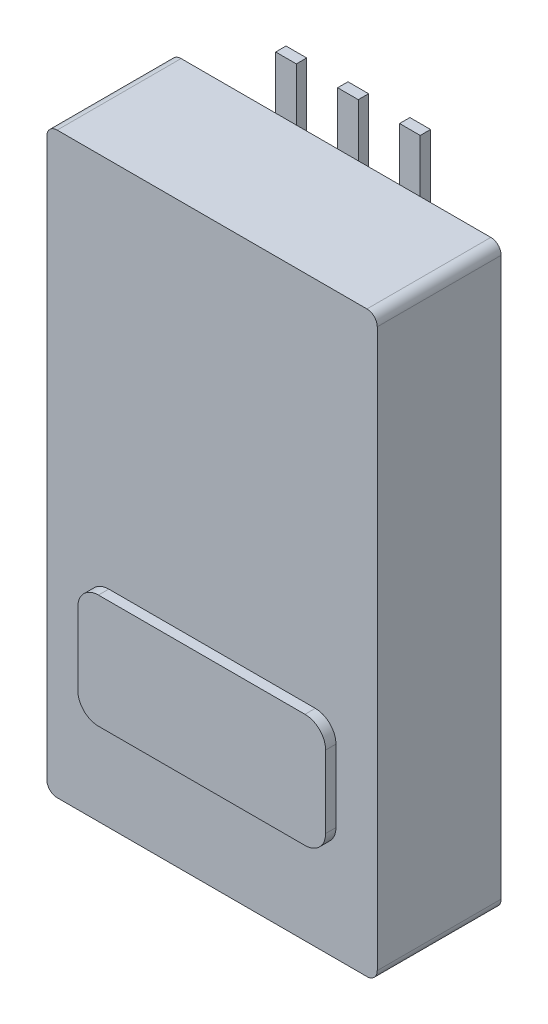
SolidWorks part; units mm, degrees
material "PE faible/moyenne densité"
ref_plane "Plan de face" through (0, 0, 0) normal (0, 0, 1) x (1, 0, 0)
ref_plane "Plan de dessus" through (0, 0, 0) normal (0, 1, 0) x (1, 0, 0)
ref_plane "Plan de droite" through (0, 0, 0) normal (1, 0, 0) x (0, 0, -1)
sketch "Esquisse1" plane through (0, 0, 0) normal (0, 0, 1) x (1, 0, 0)
  line L1 (-5.3368, 17.1111) -> (10.6632, 17.1111)
  line L2 (-5.3368, 17.1111) -> (-5.3368, -10.8889)
  line L3 (-5.3368, -10.8889) -> (10.6632, -10.8889)
  line L4 (10.6632, 17.1111) -> (10.6632, -10.8889)
  dimension "D1" = 16
  dimension "D2" = 28
extrude "Boss.-Extru.1" add sketch "Esquisse1" along normal blind 6
sketch "Esquisse2" plane through (0, 0, 6) normal (0, 0, 1) x (1, 0, 0)
  line L0 (-5.3368, -10.8889) -> (10.6632, -10.8889) construction
  line L1 (-2.3368, -0.8889) -> (7.6632, -0.8889)
  line L2 (-3.3368, -1.8889) -> (-3.3368, -5.3889)
  line L3 (-2.3368, -6.3889) -> (7.6632, -6.3889)
  line L4 (8.6632, -1.8889) -> (8.6632, -5.3889)
  line L5 (-5.3368, 17.1111) -> (-5.3368, -10.8889) construction
  arc A0 (7.6632, -0.8889) -> (8.6632, -1.8889) centre (7.6632, -1.8889) cw
  arc A1 (7.6632, -6.3889) -> (8.6632, -5.3889) centre (7.6632, -5.3889) ccw
  arc A2 (-3.3368, -5.3889) -> (-2.3368, -6.3889) centre (-2.3368, -5.3889) ccw
  arc A3 (-3.3368, -1.8889) -> (-2.3368, -0.8889) centre (-2.3368, -1.8889) cw
  point P10 (8.6632, -0.8889)
  point P15 (-3.3368, -6.3889)
  point P18 (-3.3368, -0.8889)
  dimension "D5" = 1
  dimension "D1" = 12
  dimension "D2" = 4.5
  dimension "D3" = 5.5
  dimension "D4" = 2
extrude "Boss.-Extru.2" add sketch "Esquisse2" along normal blind 0.5
fillet "Congé1" radius 0.5 4 edges at (10.6632, -10.8889, 3) (-5.3368, -10.8889, 3) (10.6632, 17.1111, 3) (-5.3368, 17.1111, 3)
sketch "Esquisse3" plane through (0, 0, 0) normal (0, 0, -1) x (-1, 0, 0)
  line L1 (-0.7446, 19.6778) -> (0.2554, 19.6778)
  line L2 (-0.7446, 19.6778) -> (-0.7446, 15.0271)
  line L3 (-0.7446, 15.0271) -> (0.2554, 15.0271)
  line L4 (0.2554, 19.6778) -> (0.2554, 15.0271)
  line L5 (-3.7446, 19.6778) -> (-2.7446, 19.6778)
  line L6 (-3.7446, 19.6778) -> (-3.7446, 15.0271)
  line L7 (-3.7446, 15.0271) -> (-2.7446, 15.0271)
  line L8 (-2.7446, 19.6778) -> (-2.7446, 15.0271)
  line L9 (-6.7446, 19.6778) -> (-5.7446, 19.6778)
  line L10 (-6.7446, 19.6778) -> (-6.7446, 15.0271)
  line L11 (-6.7446, 15.0271) -> (-5.7446, 15.0271)
  line L12 (-5.7446, 19.6778) -> (-5.7446, 15.0271)
  dimension "D1" = 1
  dimension "D2" = 1
  dimension "D3" = 1
  dimension "D4" = 2
  dimension "D5" = 2
extrude "Boss.-Extru.3" add sketch "Esquisse3" along normal blind 0.5
sketch "Esquisse4" plane through (0, 0, 0) normal (0, 0, -1) x (-1, 0, 0)
  line L1 (-3.8539, -8.7674) -> (-2.8539, -8.7674)
  line L2 (-3.8539, -8.7674) -> (-3.8539, -12.7577)
  line L3 (-3.8539, -12.7577) -> (-2.8539, -12.7577)
  line L4 (-2.8539, -8.7674) -> (-2.8539, -12.7577)
  dimension "D1" = 1
extrude "Boss.-Extru.4" add sketch "Esquisse4" along normal blind 0.5
